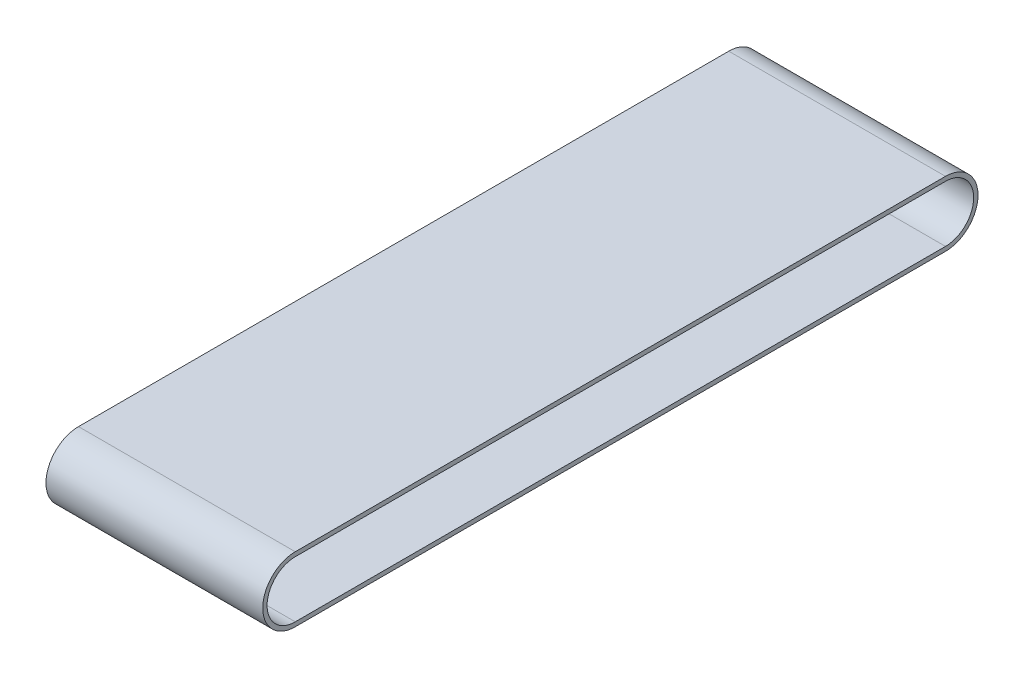
SolidWorks part; units mm, degrees
ref_plane "Front Plane" through (0, 0, 0) normal (0, 0, 1) x (1, 0, 0)
ref_plane "Top Plane" through (0, 0, 0) normal (0, 1, 0) x (1, 0, 0)
ref_plane "Right Plane" through (0, 0, 0) normal (1, 0, 0) x (0, 0, -1)
sketch "Sketch1" plane through (0, 0, 0) normal (1, 0, 0) x (0, 0, -1)
  line L0 (-183.6787, 37.8481) -> (116.3213, 37.8481)
  line L1 (-183.6787, 37.8481) -> (-183.6787, 7.8481) construction
  line L2 (-33.6787, 37.8481) -> (-33.6787, -19.5304) construction
  line L3 (-183.6787, 7.8481) -> (116.3213, 7.8481)
  line L4 (-183.6787, 9.8481) -> (116.3213, 9.8481)
  line L5 (-183.6787, 35.8481) -> (116.3213, 35.8481)
  arc A0 (-183.6787, 37.8481) -> (-183.6787, 7.8481) centre (-183.6787, 22.8481) ccw
  arc A1 (116.3213, 37.8481) -> (116.3213, 7.8481) centre (116.3213, 22.8481) cw
  arc A2 (-183.6787, 35.8481) -> (-183.6787, 9.8481) centre (-183.6787, 22.8481) ccw
  arc A3 (116.3213, 35.8481) -> (116.3213, 9.8481) centre (116.3213, 22.8481) cw
  dimension "D1" = 300
  dimension "D2" = 30
  dimension "D3" = 2
extrude "Boss-Extrude1" add sketch "Sketch1" along normal blind 100
